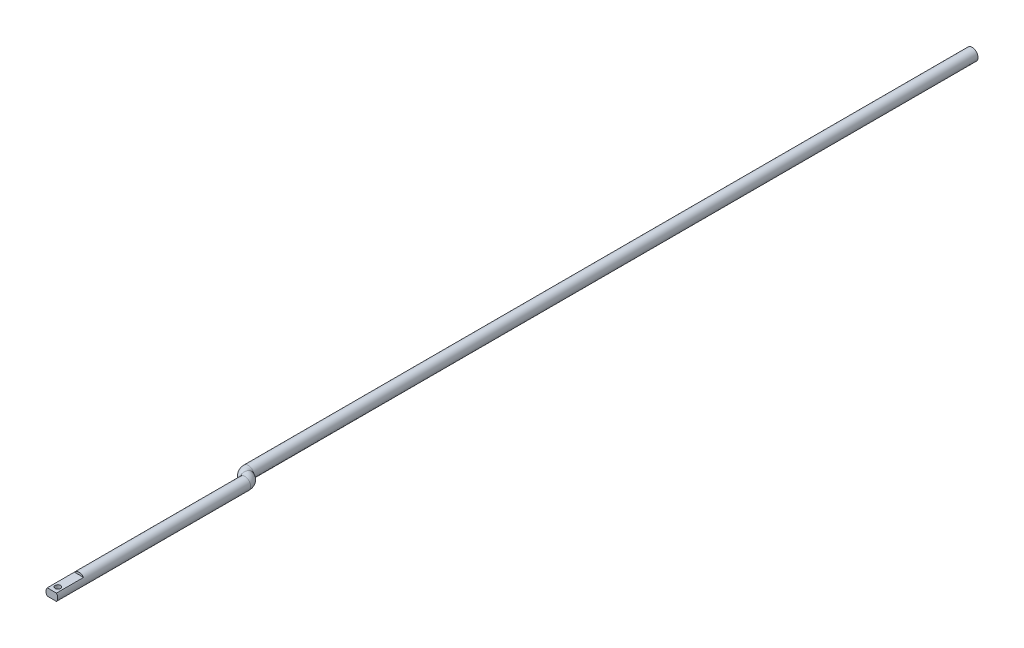
SolidWorks part; units mm, degrees
material "2024 Alloy"
ref_plane "Front Plane" through (0, 0, 0) normal (0, 0, 1) x (1, 0, 0)
ref_plane "Top Plane" through (0, 0, 0) normal (0, 1, 0) x (1, 0, 0)
ref_plane "Right Plane" through (0, 0, 0) normal (1, 0, 0) x (0, 0, -1)
sketch "Sketch1" plane through (0, 0, 0) normal (0, 0, 1) x (1, 0, 0)
  circle A0 centre (0, 0) radius 1.2319
  dimension "D1" = 2.4638
extrude "RodEnd" add sketch "Sketch1" against normal blind 40.64
sketch "Sketch2" plane through (0, 0, 0) normal (0, 0, 1) x (1, 0, 0)
  line L1 (-1.2319, -0.762) -> (1.2319, -0.762)
  line L2 (-1.2319, -0.762) -> (-1.2319, 0.762)
  line L3 (-1.2319, 0.762) -> (1.2319, 0.762)
  line L4 (1.2319, -0.762) -> (1.2319, 0.762)
  line L5 (-1.2319, -0.762) -> (1.2319, 0.762) construction
  line L6 (-1.2319, 0.762) -> (1.2319, -0.762) construction
  line L7 (-3.175, -1.2319) -> (3.175, -1.2319)
  line L8 (-3.175, -1.2319) -> (-3.175, 1.2319)
  line L9 (-3.175, 1.2319) -> (3.175, 1.2319)
  line L10 (3.175, -1.2319) -> (3.175, 1.2319)
  line L11 (-3.175, -1.2319) -> (3.175, 1.2319) construction
  line L12 (-3.175, 1.2319) -> (3.175, -1.2319) construction
  circle A0 centre (0, 0) radius 1.2319 construction
  point P0 (0, 0)
  point P8 (0, 0)
  dimension "D1" = 1.524
  dimension "D2" = 6.35
extrude "Flats" cut sketch "Sketch2" against normal blind 5.715
sketch "Sketch3" plane through (0, 0.762, 0) normal (0, 1, 0) x (1, 0, 0)
  line L0 (0.968, 0) -> (-0.968, 0) construction
  circle A0 centre (0, 1.27) radius 0.5715
  dimension "D2" = 1.143
  dimension "D1" = 1.27
extrude "Hole" cut sketch "Sketch3" against normal through all
sketch "Sketch4" plane through (0, 0, -40.64) normal (0, 0, -1) x (-1, 0, 0)
  line L0 (1.27, 0) -> (1.27, 2.0828) construction
  circle A0 centre (0, 0) radius 1.2319
  circle A1 centre (0, 0) radius 1.2319 construction
  dimension "D1" = 1.27
revolve "Rev1" add sketch "Sketch4" angle 70 about L0
sketch "Sketch6" plane through (-14.1829, 0, -5.1621) normal (-0.9397, 0, -0.342) x (-0.342, 0, 0.9397)
  line L0 (-40.2947, 0) -> (-40.2947, 2.9907) construction
  circle A0 centre (-39.0247, 0) radius 1.2319
  circle A1 centre (-39.0247, 0) radius 1.2319 construction
  dimension "D1" = 1.27
revolve "Rev2" add sketch "Sketch6" angle 70 about L0
sketch "Sketch10" plane through (0, 0, -43.0268) normal (0, 0, -1) x (-1, 0, 0)
  circle A0 centre (1.6713, 0) radius 1.2319
  circle A1 centre (1.6713, 0) radius 1.2319 construction
extrude "Shaft" add sketch "Sketch10" along normal blind 152.4
